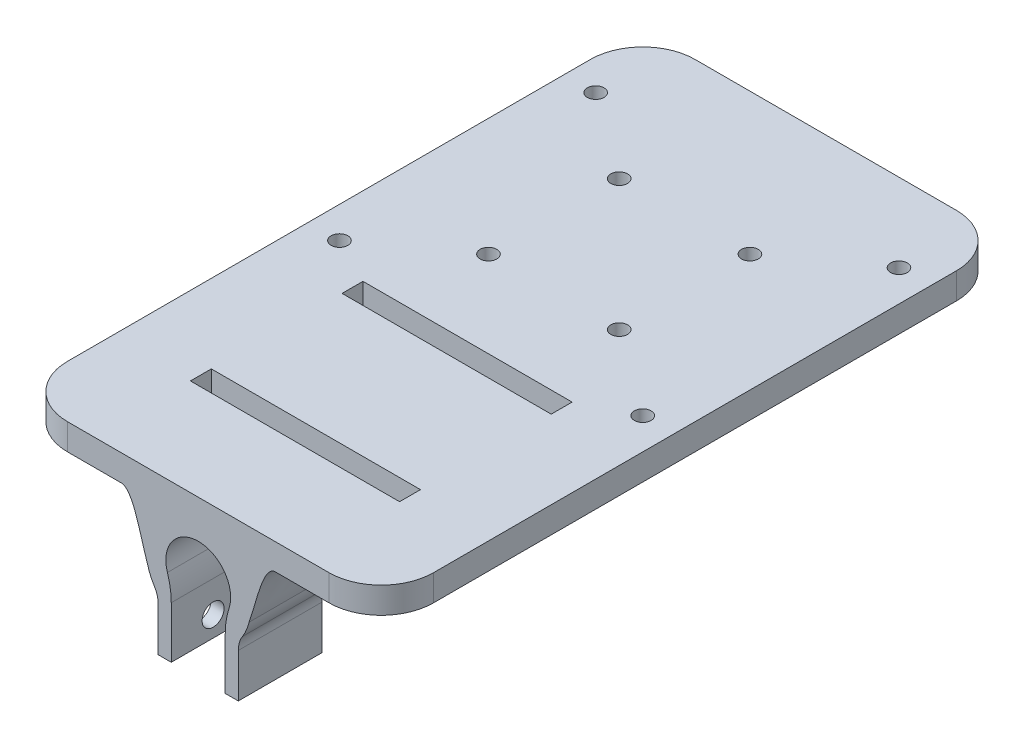
SolidWorks part; units mm, degrees
ref_plane "Front Plane" through (0, 0, 0) normal (0, 0, 1) x (1, 0, 0)
ref_plane "Top Plane" through (0, 0, 0) normal (0, 1, 0) x (1, 0, 0)
ref_plane "Right Plane" through (0, 0, 0) normal (1, 0, 0) x (0, 0, -1)
sketch "Sketch3" plane through (0, 0, 0) normal (0, 0, 1) x (1, 0, 0)
  line L0 (0, 11) -> (0, 0) construction
  line L1 (-35, 13.5) -> (35, 13.5)
  line L2 (-35, 13.5) -> (-35, 8.5)
  line L3 (-35, 8.5) -> (35, 8.5)
  line L4 (35, 13.5) -> (35, 8.5)
  line L5 (-35, 13.5) -> (35, 8.5) construction
  line L6 (-35, 8.5) -> (35, 13.5) construction
  point P0 (0, 11)
  dimension "D1" = 5
  dimension "D2" = 70
  dimension "D3" = 11
extrude "Boss-Extrude2" add sketch "Sketch3" along normal blind 120 from offset 10
sketch "Sketch1" plane through (0, 0, 0) normal (0, 0, 1) x (1, 0, 0)
  line L0 (-35, 8.5) -> (35, 8.5) construction
  line L1 (0, 0) -> (0, -9) construction
  line L2 (-14.6256, 8.5) -> (14.6256, 8.5)
  line L3 (0, 0) -> (-7.6604, -6.4279) construction
  line L4 (-35, 8.5) -> (35, 8.5) construction
  line L5 (5.1604, -16.4279) -> (5.1604, -6.5572)
  line L6 (-6.1604, -16.4279) -> (-5.1604, -16.4279)
  line L7 (-6.1604, -16.4279) -> (-7.6604, -16.4279)
  line L8 (-5.1604, -16.4279) -> (-5.1604, -6.5572)
  line L9 (-7.6604, -16.4279) -> (-7.6604, -8.0444)
  line L10 (6.1604, -16.4279) -> (7.6604, -16.4279)
  line L11 (6.1604, -16.4279) -> (5.1604, -16.4279)
  line L12 (7.6604, -16.4279) -> (7.6604, -8.0444)
  arc A0 (5.896, -1.9177) -> (-5.896, -1.9177) centre (0, 0) ccw
  arc A1 (8.4403, -5.363) -> (9.7197, -2.3512) centre (0, 0) ccw
  arc A2 (-7.6604, -8.0444) -> (-8.4403, -5.363) centre (-12.6604, -8.0444) ccw
  arc A3 (-5.1604, -6.5572) -> (-5.896, -1.9177) centre (-20.1604, -6.5572) ccw
  arc A4 (5.1604, -6.5572) -> (5.896, -1.9177) centre (20.1604, -6.5572) cw
  arc A5 (7.6604, -8.0444) -> (8.4403, -5.363) centre (12.6604, -8.0444) cw
  arc A6 (-9.7197, -2.3512) -> (-8.4403, -5.363) centre (0, 0) ccw
  spline S0 degree 3 poles (-14.6256, 8.5) (-12.253, 8.1529) (-11.0867, 1.3821) (-9.7197, -2.3512) knots 0 0 0 0 1 1 1 1
  spline S1 degree 3 poles (14.6256, 8.5) (12.253, 8.1529) (11.0867, 1.3821) (9.7197, -2.3512) knots 0 0 0 0 1 1 1 1
  point P18 (-5.1604, -3.4365)
  point P21 (5.1604, -3.4365)
  point P24 (7.6604, -6.4279)
  dimension "D1" = 12.4
  dimension "D2" = 20
  dimension "D6" = 1
  dimension "D3" = 5
  dimension "D4" = 15
  dimension "D10" = 15
  dimension "D11" = 5
  dimension "D5" = 50
  dimension "D7" = 1.5
  dimension "D8" = 10
  dimension "D9" = 12.9913
extrude "Boss-Extrude3" add sketch "Sketch1" along normal blind 8 and the other way blind 8 from offset 18
ref_plane "Plane4" through (0, 0, 70) normal (0, 0, 1) x (1, 0, 0)
sketch "Sketch4" plane through (-7.6604, 0, 0) normal (-1, 0, 0) x (0, 0, 1)
  line L0 (10, -8.0444) -> (26, -16.9992) construction
  line L1 (26, -8.0444) -> (26, -16.4279) construction
  circle A0 centre (18, -12.5218) radius 2.1
  dimension "D1" = 4.2
extrude "Cut-Extrude1" cut sketch "Sketch4" against normal blind 11
mirror "Mirror2" about plane through (0, 0, 70) normal (0, 0, 1) of "Boss-Extrude3", "Cut-Extrude1"
sketch "Sketch5" plane through (0, 13.5, 0) normal (0, 1, 0) x (1, 0, 0)
  line L0 (-16.4603, -70) -> (16.4603, -70) construction
  line L1 (-29, -25) -> (29, -25) construction
  line L2 (-29, -25) -> (-29, -74) construction
  line L3 (-29, -74) -> (29, -74) construction
  line L4 (29, -25) -> (29, -74) construction
  line L5 (-29, -25) -> (29, -74) construction
  line L6 (-29, -74) -> (29, -25) construction
  line L8 (35, -10) -> (-35, -130) construction
  line L9 (-35, -10) -> (-35, -130) construction
  line L10 (35, -130) -> (-35, -130) construction
  line L11 (35, -10) -> (-35, -10) construction
  line L14 (35, -130) -> (35, -10) construction
  circle A0 centre (29, -25) radius 1.6
  circle A1 centre (29, -74) radius 1.6
  circle A2 centre (-29, -74) radius 1.6
  circle A3 centre (-29, -25) radius 1.6
  point P0 (0, -70)
  point P23 (0, -49.5)
  dimension "D3" = 3.2
  dimension "D4" = 15
  dimension "D1" = 58
  dimension "D2" = 49
  dimension "D5" = 6
sketch "Sketch6" plane through (0, 13.5, 0) normal (0, 1, 0) x (1, 0, 0)
  line L0 (-16.4603, -70) -> (16.4603, -70) construction
  line L1 (-20, -82.5) -> (20, -82.5)
  line L2 (-20, -82.5) -> (-20, -107.5) construction
  line L3 (-20, -107.5) -> (20, -107.5)
  line L4 (20, -82.5) -> (20, -107.5) construction
  line L5 (-20, -82.5) -> (20, -107.5) construction
  line L6 (-20, -107.5) -> (20, -82.5) construction
  line L9 (-20, -82.5) -> (-20, -78.5)
  line L10 (-20, -78.5) -> (20, -78.5)
  line L11 (20, -78.5) -> (20, -89.585)
  line L12 (-20, -107.5) -> (-20, -111.5)
  line L13 (-20, -111.5) -> (20, -111.5)
  line L14 (20, -111.5) -> (20, -107.5)
  line L15 (20, -82.5) -> (20, -89.585)
  point P0 (0, -95)
  dimension "D1" = 25
  dimension "D2" = 40
  dimension "D3" = 25
  dimension "D5" = 4
  dimension "D6" = 4
sketch "Sketch7" plane through (0, 13.5, 0) normal (0, 1, 0) x (1, 0, 0)
  line L0 (0, -10) -> (0, -130) construction
  line L1 (-12.5, -37) -> (12.5, -37) construction
  line L2 (-12.5, -37) -> (-12.5, -62) construction
  line L3 (-12.5, -62) -> (12.5, -62) construction
  line L4 (12.5, -37) -> (12.5, -62) construction
  line L5 (-12.5, -37) -> (12.5, -62) construction
  line L6 (-12.5, -62) -> (12.5, -37) construction
  line L7 (35, -10) -> (-35, -10) construction
  line L8 (35, -130) -> (-35, -130) construction
  circle A0 centre (12.5, -37) radius 1.6
  circle A1 centre (12.5, -62) radius 1.6
  circle A2 centre (-12.5, -62) radius 1.6
  circle A3 centre (-12.5, -37) radius 1.6
  point P0 (0, -70)
  point P12 (0, -49.5)
  dimension "D4" = 3.2
  dimension "D1" = 25
  dimension "D2" = 25
fillet "Fillet1" radius 10 4 edges at (35, 11, 10) (35, 11, 130) (-35, 11, 130) (-35, 11, 10)
extrude "Cut-Extrude2" cut sketch "Sketch5" against normal blind 11
extrude "Cut-Extrude5" cut sketch "Sketch7" against normal up to next
extrude "Cut-Extrude6" cut sketch "Sketch6" against normal up to next contours L11 L10 L9 L1 | L13 L14 L3 L12
